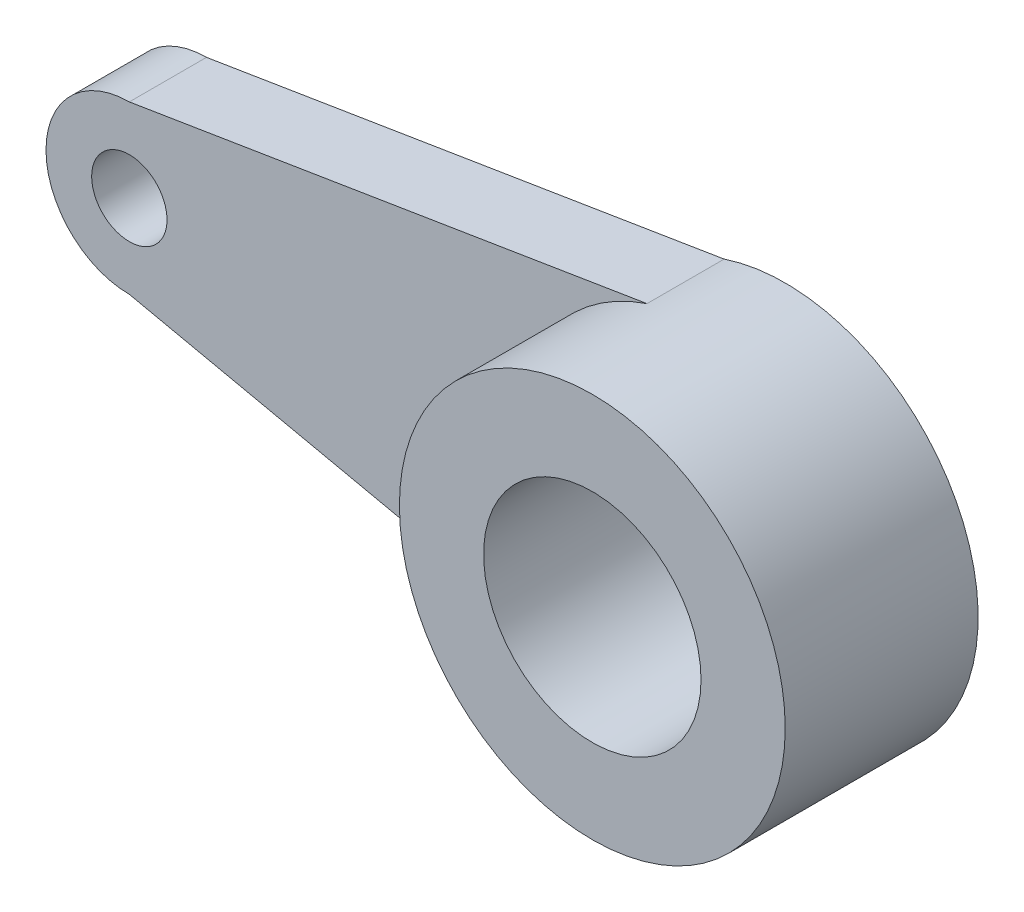
SolidWorks part; units mm, degrees
ref_plane "前视基准面" through (0, 0, 0) normal (0, 0, 1) x (1, 0, 0)
ref_plane "上视基准面" through (0, 0, 0) normal (0, 1, 0) x (1, 0, 0)
ref_plane "右视基准面" through (0, 0, 0) normal (1, 0, 0) x (0, 0, -1)
sketch "草图1" plane through (0, 0, 0) normal (0, 0, 1) x (1, 0, 0)
  circle A0 centre (20.9796, 15.1546) radius 2.8179
  circle A1 centre (20.9796, 15.1546) radius 5
  dimension "D1" = 10
extrude "凸台-拉伸1" add sketch "草图1" along normal blind 5
sketch "草图2" plane through (0, 0, 0) normal (0, 0, -1) x (-1, 0, 0)
  line L0 (-20.9796, 20.1546) -> (-5.9796, 17.7172)
  line L1 (-20.9796, 10.1546) -> (-5.9796, 13.3972)
  line L2 (-20.9796, 20.1546) -> (-17.4792, 16.1329)
  line L3 (-17.4792, 16.1329) -> (-17.8911, 13.5982)
  line L4 (-17.8911, 13.5982) -> (-20.8732, 11.0026)
  line L5 (-20.8732, 11.0026) -> (-20.9796, 10.1546)
  line L6 (-20.9796, 15.1546) -> (-20.9796, 13.5807) construction
  circle A0 centre (-5.9796, 15.5572) radius 2.16 construction
  circle A1 centre (-20.9796, 15.1546) radius 5 construction
  arc A2 (-5.9796, 17.7172) -> (-5.9796, 13.3972) centre (-5.9796, 15.5572) cw
  circle A4 centre (-5.9796, 15.5572) radius 0.9768
  dimension "D1" = 15
extrude "凸台-拉伸2" add sketch "草图2" against normal blind 2
